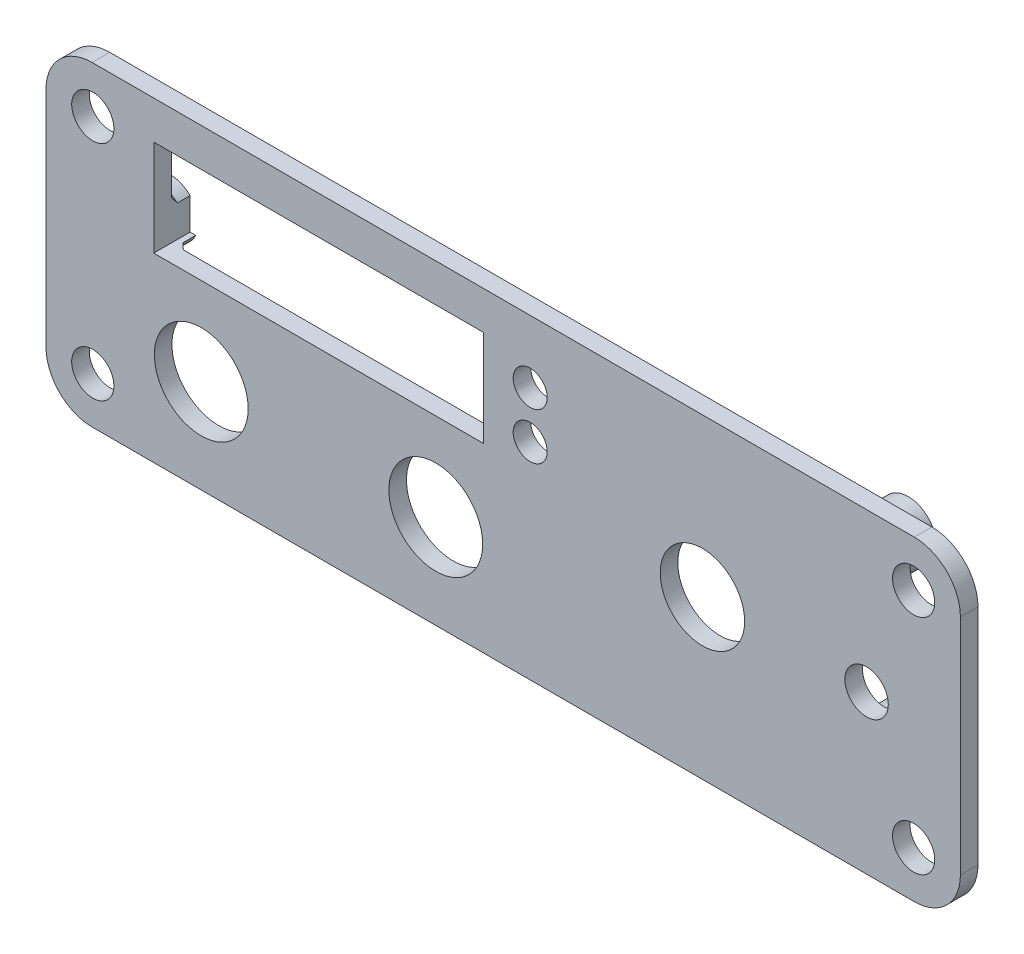
SolidWorks part; units mm, degrees
material "A-Glass Fiber"
ref_plane "Ebene vorne" through (0, 0, 0) normal (0, 0, 1) x (1, 0, 0)
ref_plane "Ebene oben" through (0, 0, 0) normal (0, 1, 0) x (1, 0, 0)
ref_plane "Ebene rechts" through (0, 0, 0) normal (1, 0, 0) x (0, 0, -1)
sketch "Sketch2" plane through (0, 0, 0) normal (0, 0, 1) x (1, 0, 0)
  line L0 (38.989, 0) -> (38.989, 26.924) construction
  line L1 (0, 13.462) -> (77.978, 13.462) construction
  line L2 (13.239, 8) -> (33.239, 8) construction
  line L3 (9.189, 19.574) -> (37.289, 19.574) construction
  line L4 (0, 22.989) -> (0, 3.935)
  line L5 (74.043, 26.924) -> (3.935, 26.924)
  line L6 (77.978, 3.935) -> (77.978, 22.989)
  line L7 (3.935, 0) -> (74.043, 0)
  line L8 (9.189, 23.674) -> (37.289, 23.674)
  line L9 (9.189, 23.674) -> (9.189, 15.474)
  line L10 (9.189, 15.474) -> (37.289, 15.474)
  line L11 (37.289, 23.674) -> (37.289, 15.474)
  line L12 (7.489, 22.962) -> (9.189, 22.962) construction
  line L13 (37.289, 22.412) -> (38.989, 22.412) construction
  circle A0 centre (3.989, 22.962) radius 1.8
  circle A1 centre (73.989, 22.962) radius 1.8
  circle A2 centre (3.989, 3.962) radius 1.8
  circle A3 centre (73.989, 3.962) radius 1.8
  arc A4 (0, 3.935) -> (3.935, 0) centre (3.935, 3.935) ccw
  arc A5 (3.935, 26.924) -> (0, 22.989) centre (3.935, 22.989) ccw
  arc A6 (77.978, 22.989) -> (74.043, 26.924) centre (74.043, 22.989) ccw
  arc A7 (74.043, 0) -> (77.978, 3.935) centre (74.043, 3.935) ccw
  circle A8 centre (3.989, 3.962) radius 3.5 construction
  circle A9 centre (55.978, 13.462) radius 3.6
  circle A10 centre (13.239, 8) radius 4
  circle A11 centre (33.239, 8) radius 4
  circle A12 centre (41.289, 21.574) radius 1.45
  circle A13 centre (41.289, 17.574) radius 1.45
  circle A14 centre (69.978, 13.462) radius 1.85
  circle A15 centre (55.978, 13.462) radius 8 construction
  circle A16 centre (13.239, 8) radius 5.65 construction
  circle A17 centre (3.989, 22.962) radius 3.5 construction
  point P29 (23.239, 15.474)
  point P35 (23.239, 8)
  dimension "D1" = 3.6
  dimension "D4" = 7.2
  dimension "D8" = 8
  dimension "D9" = 8
  dimension "D13" = 2.9
  dimension "D16" = 3.7
  dimension "D17" = 16
  dimension "D19" = 7
  dimension "D20" = 11.3
  dimension "D23" = 3.935
  dimension "D2" = 70
  dimension "D3" = 19
  dimension "D5" = 22
  dimension "D6" = 8
  dimension "D7" = 20
  dimension "D10" = 8.2
  dimension "D11" = 28.1
  dimension "D12" = 3.25
  dimension "D14" = 4
  dimension "D15" = 4
  dimension "D18" = 8
  dimension "D21" = 26.924
  dimension "D22" = 77.978
extrude "Boss-Extrude2" add sketch "Sketch2" along normal blind 1.5 separate body
sketch "Sketch3" plane through (0, 0, 0) normal (0, 0, -1) x (-1, 0, 0)
  line L0 (-8.389, 16.474) -> (-9.189, 16.474) construction
  line L1 (-9.189, 23.674) -> (-9.189, 15.474) construction
  line L3 (-41.289, 21.574) -> (-41.289, 17.574) construction
  line L4 (-9.189, 15.474) -> (-9.6707, 15.474)
  line L5 (-9.189, 15.474) -> (-37.289, 15.474) construction
  line L6 (-9.189, 15.474) -> (-9.189, 18.1681)
  circle A0 centre (-7.489, 16.474) radius 0.9
  arc A1 (-9.6707, 15.474) -> (-9.189, 18.1681) centre (-7.489, 16.474) ccw
  circle A2 centre (-46.239, 22.674) radius 0.9
  circle A3 centre (-46.239, 22.674) radius 2.4
  point P15 (-41.289, 19.574)
  point P16 (-9.189, 19.574)
  dimension "D1" = 1.8
  dimension "D2" = 4.8
  dimension "D4" = 4.95
  dimension "D3" = 1.7
  dimension "D5" = 3.1
  dimension "D6" = 3.1
extrude "Boss-Extrude3" add sketch "Sketch3" along normal blind 1.6
sketch "Sketch4" plane through (0, 0, 0) normal (0, 0, -1) x (-1, 0, 0)
  circle A0 centre (-67.228, 20.962) radius 0.9
  circle A2 centre (-67.228, 20.962) radius 2.4
  circle A4 centre (-69.978, 13.462) radius 1.85 construction
  circle A5 centre (-67.228, 5.962) radius 0.9
  circle A6 centre (-67.228, 5.962) radius 2.4
  circle A7 centre (-45.728, 5.962) radius 0.9
  circle A8 centre (-45.728, 5.962) radius 2.4
  dimension "D1" = 4.8
  dimension "D2" = 1.8
  dimension "D3" = 2.75
  dimension "D4" = 7.5
  dimension "D5" = 15
  dimension "D6" = 21.5
extrude "Boss-Extrude4" add sketch "Sketch4" along normal blind 4.8
chamfer "Chamfer1" distance 0.5 angle 45 5 edges at (5.1265, 16.0515, 0) (48.639, 22.674, 0) (48.128, 5.962, 0) (69.628, 20.962, 0) (69.628, 5.962, 0)
